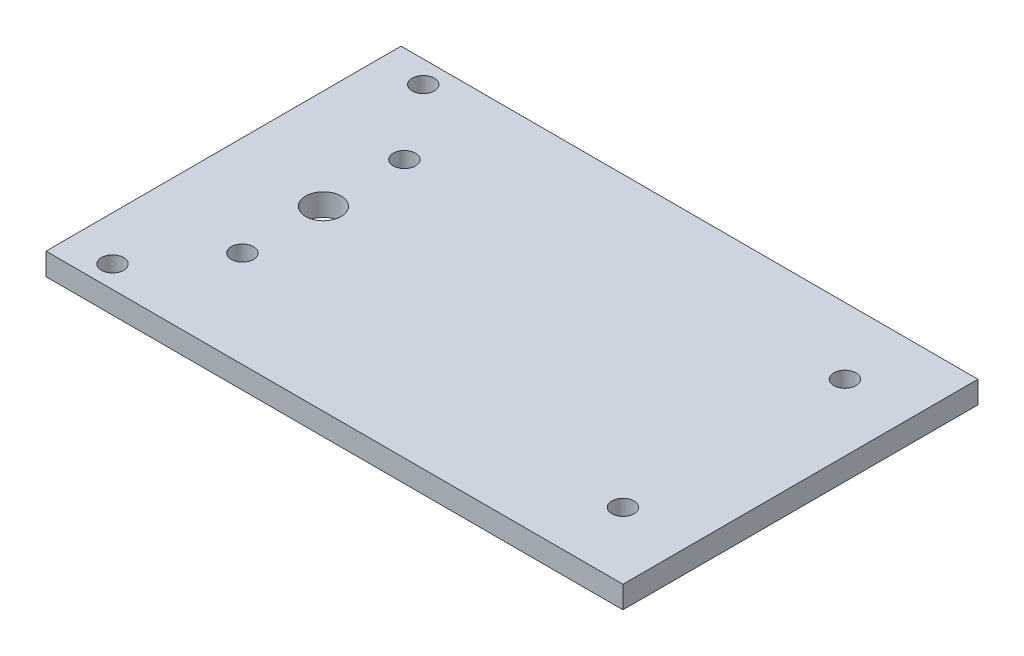
SolidWorks part; units mm, degrees
ref_plane "Front Plane" through (0, 0, 0) normal (0, 0, 1) x (1, 0, 0)
ref_plane "Top Plane" through (0, 0, 0) normal (0, 1, 0) x (1, 0, 0)
ref_plane "Right Plane" through (0, 0, 0) normal (1, 0, 0) x (0, 0, -1)
sketch "Sketch1" plane through (0, 0, 0) normal (0, 1, 0) x (1, 0, 0)
  line L0 (-69.7183, -5.3521) -> (60.2817, -5.3521) construction
  line L1 (-69.7183, 34.6479) -> (60.2817, 34.6479)
  line L2 (-69.7183, 34.6479) -> (-69.7183, -45.3521)
  line L3 (-69.7183, -45.3521) -> (60.2817, -45.3521)
  line L4 (60.2817, 34.6479) -> (60.2817, -45.3521)
  line L5 (-47.2183, -5.3521) -> (-47.2183, 47.2908) construction
  circle A0 centre (-47.2183, -5.3521) radius 4
  circle A1 centre (45.2817, 19.6479) radius 2.5
  circle A2 centre (-59.7183, 29.6479) radius 2.5
  circle A3 centre (45.2817, -30.3521) radius 2.5
  circle A4 centre (-59.7183, -40.3521) radius 2.5
  circle A5 centre (-47.2183, 12.8979) radius 2.5
  circle A6 centre (-47.2183, -23.6021) radius 2.5
  dimension "D3" = 8
  dimension "D4" = 5
  dimension "D5" = 5
  dimension "D6" = 15
  dimension "D7" = 15
  dimension "D8" = 5
  dimension "D9" = 10
  dimension "D10" = 22.5
  dimension "D11" = 5
  dimension "D12" = 18.25
  dimension "D1" = 130
  dimension "D2" = 80
extrude "Boss-Extrude1" add sketch "Sketch1" along normal blind 5
